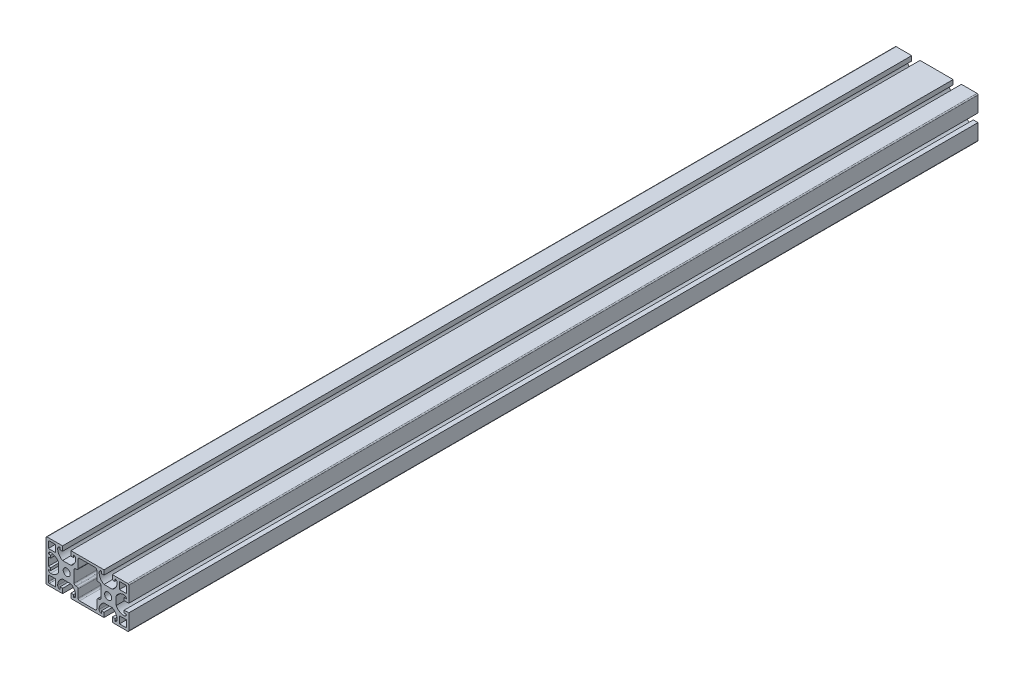
SolidWorks part; units mm, degrees
material "3.0255 (EN-AW 1350A)"
ref_plane "Płaszczyzna przednia" through (0, 0, 0) normal (0, 0, 1) x (1, 0, 0)
ref_plane "Płaszczyzna górna" through (0, 0, 0) normal (0, 1, 0) x (1, 0, 0)
ref_plane "Płaszczyzna prawa" through (0, 0, 0) normal (1, 0, 0) x (0, 0, -1)
sketch "Szkic1" plane through (0, 0, 0) normal (0, 0, 1) x (1, 0, 0)
  line L0 (0, 20) -> (0, -20) construction
  line L1 (-51.8865, 0) -> (40, 0) construction
  line L4 (-40, -19) -> (-40, 19)
  line L7 (-40, -20) -> (0, 0) construction
  line L8 (-40, 20) -> (40, -20) construction
  line L13 (20, 20) -> (20, 0) construction
  line L15 (24, 20) -> (24, 15.5)
  line L16 (24, 15.5) -> (26.4714, 15.5)
  line L21 (16, 15.5) -> (13.5286, 15.5)
  line L23 (16, 20) -> (13.5286, 20)
  line L24 (16, 20) -> (16, 15.5)
  line L25 (16, 7.75) -> (24, 7.75)
  line L26 (13.5286, 15.5) -> (13.5286, 17.75)
  line L27 (26.4714, 15.5) -> (26.4714, 17.75)
  line L28 (-24, 20) -> (-24, 15.5)
  line L29 (-26.4714, 15.5) -> (-26.4714, 17.75)
  line L30 (-24, 15.5) -> (-26.4714, 15.5)
  line L31 (-13.5286, 15.5) -> (-13.5286, 17.75)
  line L32 (-16, 15.5) -> (-13.5286, 15.5)
  line L33 (-16, 20) -> (-16, 15.5)
  line L34 (-16, 7.75) -> (-24, 7.75)
  line L35 (20, -20) -> (20, 0) construction
  line L36 (-40, -20) -> (0, 0) construction
  line L37 (-40, 20) -> (40, -20) construction
  line L38 (30.9714, -17.75) -> (36.75, -17.75)
  line L39 (-16, -7.75) -> (-24, -7.75)
  line L40 (-16, -20) -> (-16, -15.5)
  line L41 (-16, -15.5) -> (-13.5286, -15.5)
  line L42 (-13.5286, -15.5) -> (-13.5286, -17.75)
  line L43 (-24, -15.5) -> (-26.4714, -15.5)
  line L44 (-26.4714, -15.5) -> (-26.4714, -17.75)
  line L45 (-24, -20) -> (-24, -15.5)
  line L46 (26.4714, -15.5) -> (26.4714, -17.75)
  line L47 (13.5286, -15.5) -> (13.5286, -17.75)
  line L48 (16, -7.75) -> (24, -7.75)
  line L49 (16, -20) -> (16, -15.5)
  line L50 (16, -15.5) -> (13.5286, -15.5)
  line L51 (24, -15.5) -> (26.4714, -15.5)
  line L52 (24, -20) -> (24, -15.5)
  line L53 (40, -20) -> (0, 20) construction
  line L54 (35.5, 6.4714) -> (37.75, 6.4714)
  line L55 (35.5, 4) -> (35.5, 6.4714)
  line L56 (40, 4) -> (35.5, 4)
  line L57 (40, -4) -> (35.5, -4)
  line L58 (35.5, -4) -> (35.5, -6.4714)
  line L59 (35.5, -6.4714) -> (37.75, -6.4714)
  line L60 (27.75, 4) -> (27.75, -4)
  line L61 (-35.5, -6.4714) -> (-37.75, -6.4714)
  line L62 (-37.75, -4) -> (-35.5, -4)
  line L63 (-35.5, -4) -> (-35.5, -6.4714)
  line L64 (-35.5, 4) -> (-35.5, 6.4714)
  line L65 (-35.5, 6.4714) -> (-37.75, 6.4714)
  line L66 (-37.75, 4) -> (-35.5, 4)
  line L67 (-27.75, 4) -> (-27.75, -4)
  line L68 (-37.75, 4) -> (-37.75, -4)
  line L69 (40, -4) -> (40, -19)
  line L70 (40, 19) -> (40, 4)
  line L71 (-39, -20) -> (-24, -20)
  line L72 (-16, -20) -> (16, -20)
  line L73 (24, -20) -> (39, -20)
  line L74 (13.5286, 20) -> (-16, 20)
  line L75 (-24, 20) -> (-39, 20)
  line L76 (24, 20) -> (39, 20)
  line L77 (10.5286, 7.0902) -> (11.4095, 7.0902)
  line L78 (-7.5286, -17.75) -> (7.5286, -17.75)
  line L79 (-9.0286, -16.25) -> (-9.0286, -8.5902)
  line L80 (-7.5286, 17.75) -> (7.5286, 17.75)
  line L81 (9.0286, -16.25) -> (9.0286, -8.5902)
  line L82 (-9.0286, -17.75) -> (9.0286, 17.75) construction
  line L83 (-9.0286, 17.75) -> (9.0286, -17.75) construction
  line L84 (-11.4095, -7.0902) -> (-10.5286, -7.0902)
  line L85 (-12.9095, -5.5902) -> (-12.9095, 5.5902)
  line L86 (-11.4095, 7.0902) -> (-10.5286, 7.0902)
  line L87 (12.9095, -5.5902) -> (12.9095, 5.5902)
  line L88 (-12.9095, -7.0902) -> (0, 0) construction
  line L89 (-12.9095, 7.0902) -> (12.9095, -7.0902) construction
  line L90 (-9.0286, 8.5902) -> (-9.0286, 16.25)
  line L91 (-9.0286, 4.5143) -> (-9.0286, 4.9587)
  line L92 (-9.0286, -4.9587) -> (-9.0286, -4.5143)
  line L93 (9.0286, 8.5902) -> (9.0286, 16.25)
  line L94 (10.5286, -7.0902) -> (11.4095, -7.0902)
  line L96 (0, 0) -> (12.9095, 7.0902) construction
  line L98 (37.75, -10.9714) -> (37.75, -16.75)
  line L99 (30.9714, 10.9714) -> (37.75, 10.9714)
  line L100 (30.9714, 10.9714) -> (30.9714, 17.75)
  line L101 (30.9714, 17.75) -> (36.75, 17.75)
  line L102 (37.75, 10.9714) -> (37.75, 16.75)
  line L103 (30.9714, 10.9714) -> (37.75, 17.75) construction
  line L104 (30.9714, 17.75) -> (37.75, 10.9714) construction
  line L105 (30.9714, -10.9714) -> (37.75, -10.9714)
  line L106 (30.9714, -10.9714) -> (30.9714, -17.75)
  line L107 (-30.9714, -10.9714) -> (-30.9714, -17.75)
  line L108 (-30.9714, -10.9714) -> (-37.75, -10.9714)
  line L109 (-37.75, -10.9714) -> (-37.75, -16.75)
  line L110 (-30.9714, -17.75) -> (-36.75, -17.75)
  line L111 (-30.9714, 17.75) -> (-36.75, 17.75)
  line L112 (-37.75, 10.9714) -> (-37.75, 16.75)
  line L113 (-30.9714, 10.9714) -> (-37.75, 10.9714)
  line L114 (-30.9714, 10.9714) -> (-30.9714, 17.75)
  circle A0 centre (-20, 0) radius 3.4
  circle A1 centre (20, 0) radius 3.4
  arc A2 (26.4714, 17.75) -> (28.7214, 15.5) centre (26.4714, 15.5) cw
  arc A3 (28.7214, 15.5) -> (24, 7.75) centre (20, 15.5) cw
  arc A4 (13.5286, 17.75) -> (11.2786, 15.5) centre (13.5286, 15.5) ccw
  arc A5 (11.2786, 15.5) -> (16, 7.75) centre (20, 15.5) ccw
  arc A6 (-26.4714, 17.75) -> (-28.7214, 15.5) centre (-26.4714, 15.5) ccw
  arc A7 (-13.5286, 17.75) -> (-11.2786, 15.5) centre (-13.5286, 15.5) cw
  arc A8 (-11.2786, 15.5) -> (-16, 7.75) centre (-20, 15.5) cw
  arc A9 (-28.7214, 15.5) -> (-24, 7.75) centre (-20, 15.5) ccw
  arc A10 (-28.7214, -15.5) -> (-24, -7.75) centre (-20, -15.5) cw
  arc A11 (-11.2786, -15.5) -> (-16, -7.75) centre (-20, -15.5) ccw
  arc A12 (-13.5286, -17.75) -> (-11.2786, -15.5) centre (-13.5286, -15.5) ccw
  arc A13 (-26.4714, -17.75) -> (-28.7214, -15.5) centre (-26.4714, -15.5) cw
  arc A14 (11.2786, -15.5) -> (16, -7.75) centre (20, -15.5) cw
  arc A15 (13.5286, -17.75) -> (11.2786, -15.5) centre (13.5286, -15.5) cw
  arc A16 (28.7214, -15.5) -> (24, -7.75) centre (20, -15.5) ccw
  arc A17 (26.4714, -17.75) -> (28.7214, -15.5) centre (26.4714, -15.5) ccw
  arc A18 (35.5, 8.7214) -> (27.75, 4) centre (35.5, 0) ccw
  arc A19 (37.75, 6.4714) -> (35.5, 8.7214) centre (35.5, 6.4714) ccw
  arc A20 (37.75, -6.4714) -> (35.5, -8.7214) centre (35.5, -6.4714) cw
  arc A21 (35.5, -8.7214) -> (27.75, -4) centre (35.5, 0) cw
  arc A22 (-35.5, -8.7214) -> (-27.75, -4) centre (-35.5, 0) ccw
  arc A23 (-37.75, -6.4714) -> (-35.5, -8.7214) centre (-35.5, -6.4714) ccw
  arc A24 (-37.75, 6.4714) -> (-35.5, 8.7214) centre (-35.5, 6.4714) cw
  arc A25 (-35.5, 8.7214) -> (-27.75, 4) centre (-35.5, 0) cw
  arc A26 (-10.5286, 7.0902) -> (-9.0286, 8.5902) centre (-10.5286, 8.5902) ccw
  arc A27 (-9.0286, -8.5902) -> (-10.5286, -7.0902) centre (-10.5286, -8.5902) ccw
  arc A28 (11.4095, -7.0902) -> (12.9095, -5.5902) centre (11.4095, -5.5902) ccw
  arc A29 (9.0286, -8.5902) -> (10.5286, -7.0902) centre (10.5286, -8.5902) cw
  arc A30 (7.5286, -17.75) -> (9.0286, -16.25) centre (7.5286, -16.25) ccw
  arc A31 (-7.5286, -17.75) -> (-9.0286, -16.25) centre (-7.5286, -16.25) cw
  arc A32 (-11.4095, -7.0902) -> (-12.9095, -5.5902) centre (-11.4095, -5.5902) cw
  arc A33 (-12.9095, 5.5902) -> (-11.4095, 7.0902) centre (-11.4095, 5.5902) cw
  arc A34 (-9.0286, 16.25) -> (-7.5286, 17.75) centre (-7.5286, 16.25) cw
  arc A35 (7.5286, 17.75) -> (9.0286, 16.25) centre (7.5286, 16.25) cw
  arc A36 (11.4095, 7.0902) -> (12.9095, 5.5902) centre (11.4095, 5.5902) cw
  arc A37 (10.5286, 7.0902) -> (9.0286, 8.5902) centre (10.5286, 8.5902) cw
  arc A38 (-40, 19) -> (-39, 20) centre (-39, 19) cw
  arc A39 (-39, -20) -> (-40, -19) centre (-39, -19) cw
  arc A40 (39, -20) -> (40, -19) centre (39, -19) ccw
  arc A41 (39, 20) -> (40, 19) centre (39, 19) cw
  arc A42 (36.75, 17.75) -> (37.75, 16.75) centre (36.75, 16.75) cw
  arc A43 (36.75, -17.75) -> (37.75, -16.75) centre (36.75, -16.75) ccw
  arc A44 (-36.75, -17.75) -> (-37.75, -16.75) centre (-36.75, -16.75) cw
  arc A45 (-36.75, 17.75) -> (-37.75, 16.75) centre (-36.75, 16.75) ccw
  point P5 (0, 0)
  point P17 (0, 0)
  point P30 (24, 17.75)
  point P108 (0, 0)
  point P124 (-9.0286, 7.0902)
  point P132 (9.0286, -7.0902)
  point P156 (9.0286, 7.0902)
  point P161 (40, 20)
  point P162 (34.3607, 14.3607)
  dimension "D4" = 6.8
  dimension "D5" = 12.25
  dimension "D9" = 11
  dimension "D11" = 1.5
  dimension "D12" = 1
  dimension "D16" = 1
  dimension "D1" = 80
  dimension "D2" = 40
  dimension "D3" = 40
  dimension "D6" = 2.25
  dimension "D7" = 8
  dimension "D8" = 4.5
  dimension "D10" = 14.1804
  dimension "D13" = 2.25
  dimension "D14" = 2.25
  dimension "D15" = 2.25
extrude "Dodanie-wyciągnięcie1" add sketch "Szkic1" along normal blind 820 contours A20 A21 L60 A18 A19 L54 L55 L56 L70 L76 L15 L16 L27 A2 A3 L25 A5 A4 L26 L21 L24 L23 L74 L33 L32 L31 A7 A8 L34 A9 A6 L29 L30 L28 L75 L4 L71 L45 L43 L44 A13 A10 L39 A11 A12 L42 L41 L40 L72 L49 L50
